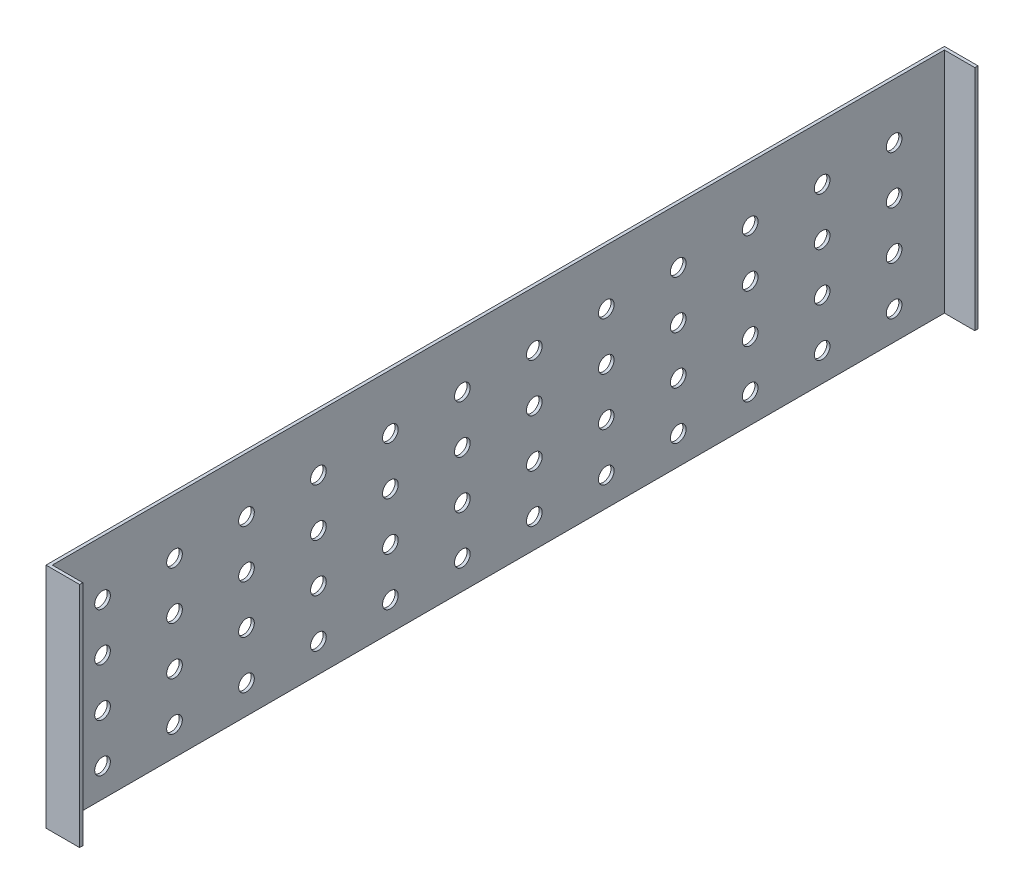
SolidWorks part; units mm, degrees
ref_plane "Front Plane" through (0, 0, 0) normal (0, 0, 1) x (1, 0, 0)
ref_plane "Top Plane" through (0, 0, 0) normal (0, 1, 0) x (1, 0, 0)
ref_plane "Right Plane" through (0, 0, 0) normal (1, 0, 0) x (0, 0, -1)
sketch "Sketch1" plane through (0, 0, 0) normal (1, 0, 0) x (0, 0, -1)
  line L0 (-165, 30) -> (165, -30) construction
  line L1 (-165, -30) -> (-135, -30) construction
  line L2 (-165, -30) -> (-165, -10) construction
  line L4 (-187.2628, 53) -> (187.2628, 53)
  line L5 (-187.2628, 53) -> (-187.2628, -42)
  line L6 (-187.2628, -42) -> (187.2628, -42)
  line L7 (187.2628, 53) -> (187.2628, -42)
  circle A0 centre (-165, -30) radius 3.2639
  circle A1 centre (-135, -30) radius 3.2639
  circle A2 centre (-105, -30) radius 3.2639
  circle A3 centre (-75, -30) radius 3.2639
  circle A4 centre (-45, -30) radius 3.2639
  circle A5 centre (-15, -30) radius 3.2639
  circle A6 centre (15, -30) radius 3.2639
  circle A7 centre (45, -30) radius 3.2639
  circle A8 centre (75, -30) radius 3.2639
  circle A9 centre (105, -30) radius 3.2639
  circle A10 centre (135, -30) radius 3.2639
  circle A11 centre (165, -30) radius 3.2639
  circle A12 centre (-135, -10) radius 3.2639
  circle A13 centre (-105, -10) radius 3.2639
  circle A14 centre (-75, -10) radius 3.2639
  circle A15 centre (-45, -10) radius 3.2639
  circle A16 centre (-15, -10) radius 3.2639
  circle A17 centre (15, -10) radius 3.2639
  circle A18 centre (45, -10) radius 3.2639
  circle A19 centre (75, -10) radius 3.2639
  circle A20 centre (105, -10) radius 3.2639
  circle A21 centre (135, -10) radius 3.2639
  circle A22 centre (165, -10) radius 3.2639
  circle A23 centre (-135, 10) radius 3.2639
  circle A24 centre (-105, 10) radius 3.2639
  circle A25 centre (-75, 10) radius 3.2639
  circle A26 centre (-45, 10) radius 3.2639
  circle A27 centre (-15, 10) radius 3.2639
  circle A28 centre (15, 10) radius 3.2639
  circle A29 centre (45, 10) radius 3.2639
  circle A30 centre (75, 10) radius 3.2639
  circle A31 centre (105, 10) radius 3.2639
  circle A32 centre (135, 10) radius 3.2639
  circle A33 centre (165, 10) radius 3.2639
  circle A34 centre (-135, 30) radius 3.2639
  circle A35 centre (-105, 30) radius 3.2639
  circle A36 centre (-75, 30) radius 3.2639
  circle A37 centre (-45, 30) radius 3.2639
  circle A38 centre (-15, 30) radius 3.2639
  circle A39 centre (15, 30) radius 3.2639
  circle A40 centre (45, 30) radius 3.2639
  circle A41 centre (75, 30) radius 3.2639
  circle A42 centre (105, 30) radius 3.2639
  circle A43 centre (135, 30) radius 3.2639
  circle A44 centre (165, 30) radius 3.2639
  circle A45 centre (-165, -10) radius 3.2639
  circle A46 centre (-165, 10) radius 3.2639
  circle A47 centre (-165, 30) radius 3.2639
  circle A48 centre (-165, 30) radius 7 construction
  circle A49 centre (-165, -30) radius 7 construction
  point P3 (0, 0)
  point P107 (0, -42)
  dimension "D1" = 6.5278
  dimension "D6" = 14
  dimension "D4" = 30
  dimension "D5" = 20
  dimension "D7" = 95
  dimension "D8" = 42
  dimension "D9" = 374.5255
  dimension "D2" = 12
  dimension "D3" = 4
extrude "Boss-Extrude1" add sketch "Sketch1" along normal blind 1.3106
sketch "Sketch2" plane through (1.3106, 0, 0) normal (1, 0, 0) x (0, 0, -1)
  line L0 (-187.2628, -42) -> (187.2628, -42) construction
  line L1 (-187.2628, 53) -> (-185.9521, 53)
  line L2 (-187.2628, 53) -> (-187.2628, -42)
  line L3 (-187.2628, -42) -> (-185.9521, -42)
  line L4 (-185.9521, 53) -> (-185.9521, -42)
  line L5 (187.2628, 53) -> (-187.2628, 53) construction
  line L6 (187.2628, 53) -> (185.9521, 53)
  line L7 (187.2628, 53) -> (187.2628, -42)
  line L8 (187.2628, -42) -> (185.9521, -42)
  line L9 (185.9521, 53) -> (185.9521, -42)
  dimension "D1" = 1.3106
extrude "Boss-Extrude2" add sketch "Sketch2" along normal blind 12.7
